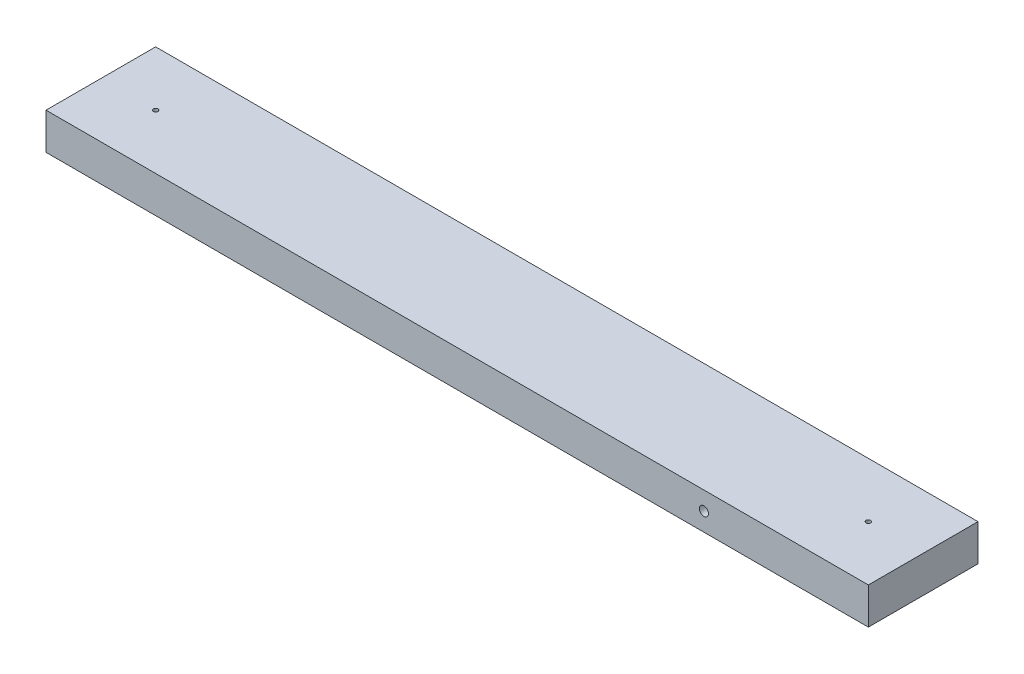
SolidWorks part; units mm, degrees
ref_plane "Front Plane" through (0, 0, 0) normal (0, 0, 1) x (1, 0, 0)
ref_plane "Top Plane" through (0, 0, 0) normal (0, 1, 0) x (1, 0, 0)
ref_plane "Right Plane" through (0, 0, 0) normal (1, 0, 0) x (0, 0, -1)
sketch "Sketch1" plane through (0, 0, 0) normal (1, 0, 0) x (0, 0, -1)
  line L1 (-152.4, 50.8) -> (152.4, 50.8)
  line L2 (-152.4, 50.8) -> (-152.4, -50.8)
  line L3 (-152.4, -50.8) -> (152.4, -50.8)
  line L4 (152.4, 50.8) -> (152.4, -50.8)
  line L5 (-152.4, 50.8) -> (152.4, -50.8) construction
  line L6 (-152.4, -50.8) -> (152.4, 50.8) construction
  point P0 (0, 0)
  dimension "D1" = 101.6
  dimension "D2" = 304.8
extrude "Boss-Extrude1" add sketch "Sketch1" along normal blind 2286
sketch "Sketch2" plane through (0, 0, 152.4) normal (0, 0, 1) x (1, 0, 0)
  line L0 (0, 50.8) -> (0, -50.8) construction
  circle A0 centre (1828.8, 0) radius 12.7
  dimension "D1" = 25.4
  dimension "D2" = 1828.8
extrude "Cut-Extrude1" cut sketch "Sketch2" against normal up to surface (304.8 mm away) up to face at (1143, 0, -152.4)
sketch "Sketch3" plane through (0, 50.8, 0) normal (0, 1, 0) x (1, 0, 0)
  line L0 (2286, 152.4) -> (2286, -152.4) construction
  circle A0 centre (2133.6, 0) radius 6.35
  dimension "D2" = 12.7
  dimension "D1" = 152.4
extrude "Cut-Extrude2" cut sketch "Sketch3" against normal up to surface (101.6 mm away) up to face at (1143, -50.8, 0)
sketch "Sketch4" plane through (0, -50.8, 0) normal (0, -1, 0) x (1, 0, 0)
  line L0 (0, 152.4) -> (0, -152.4) construction
  circle A0 centre (152.4, 0) radius 6.35
  dimension "D1" = 12.7
  dimension "D2" = 152.4
extrude "Cut-Extrude3" cut sketch "Sketch4" against normal up to surface (101.6 mm away) up to face at (2133.6, 50.8, 6.35)
